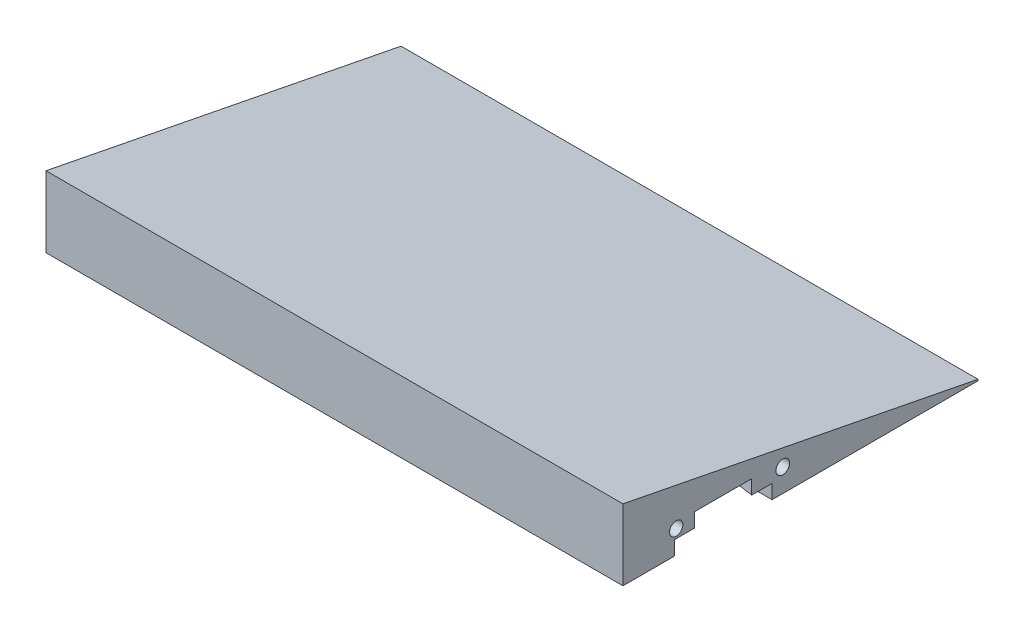
SolidWorks part; units mm, degrees
ref_plane "Front Plane" through (0, 0, 0) normal (0, 0, 1) x (1, 0, 0)
ref_plane "Top Plane" through (0, 0, 0) normal (0, 1, 0) x (1, 0, 0)
ref_plane "Right Plane" through (0, 0, 0) normal (1, 0, 0) x (0, 0, -1)
sketch "Sketch1" plane through (0, 0, 0) normal (1, 0, 0) x (0, 0, -1)
  line L0 (0, 0) -> (0, 20.32)
  line L1 (0, 20.32) -> (101.6, 0.4)
  line L2 (101.6, 0.4) -> (101.6, 0)
  line L3 (101.6, 0) -> (0, 0)
  dimension "D1" = 0.4
  dimension "D2" = 101.6
  dimension "D3" = 20.32
extrude "Boss-Extrude1" add sketch "Sketch1" along normal mid plane 391.16
sketch "Sketch2" plane through (195.58, 0, 0) normal (1, 0, 0) x (0, 0, -1)
  line L0 (0, 0) -> (101.6, 0) construction
  line L3 (0, 20.32) -> (0, 0) construction
  circle A0 centre (9.652, 3.81) radius 3.3147
  circle A1 centre (47.752, 3.81) radius 3.3147
  circle A3 centre (9.652, 3.81) radius 3.81 construction
  dimension "D1" = 38.1
  dimension "D2" = 6.6294
  dimension "D3" = 9.652
  dimension "D4" = 3.81
extrude "Cut-Extrude1" cut sketch "Sketch2" against normal blind 38.1
mirror "Mirror3" about plane through (0, 0, 0) normal (1, 0, 0) of "Cut-Extrude1"
sketch "Sketch3" plane through (-195.58, 0, 0) normal (-1, 0, 0) x (0, 0, 1)
  line L5 (0, 0) -> (-101.6, 0) construction
  line L6 (-42.672, 4.064) -> (-14.732, 4.064)
  line L7 (-42.672, 4.064) -> (-42.672, 0)
  line L8 (-42.672, 0) -> (-14.732, 0)
  line L9 (-14.732, 4.064) -> (-14.732, 0)
  line L10 (0, 20.32) -> (0, 0) construction
  dimension "D1" = 27.94
  dimension "D2" = 4.064
  dimension "D3" = 0
  dimension "D4" = 14.732
extrude "Cut-Extrude2" cut sketch "Sketch3" against normal through all
sketch "Sketch4" plane through (0, 0, 0) normal (0, -1, 0) x (1, 0, 0)
  line L0 (-144.78, -42.672) -> (-146.1056, -52.1043)
  line L1 (195.58, -42.672) -> (-195.58, -42.672) construction
  line L2 (-144.78, -42.672) -> (-128.5844, -42.672)
  line L5 (-144.78, -42.672) -> (-144.78, -52.1043) construction
  line L6 (-128.5844, -42.672) -> (-127.2588, -52.1043)
  line L7 (-128.5844, -42.672) -> (-128.5844, -52.1043) construction
  line L8 (-144.78, -52.1043) -> (-128.5844, -52.1043)
  line L9 (-144.78, -52.1043) -> (-146.1056, -52.1043)
  line L10 (-128.5844, -52.1043) -> (-127.2588, -52.1043)
  line L11 (-195.58, -42.672) -> (-195.58, -101.6) construction
  line L12 (-77.5812, -42.672) -> (-78.9069, -52.1043)
  line L13 (-77.5812, -52.1043) -> (-78.9069, -52.1043)
  line L14 (-77.5812, -52.1043) -> (-61.3857, -52.1043)
  line L15 (-61.3857, -52.1043) -> (-60.0601, -52.1043)
  line L16 (-61.3857, -42.672) -> (-60.0601, -52.1043)
  line L17 (-77.5812, -42.672) -> (-61.3857, -42.672)
  line L18 (-10.3825, -42.672) -> (-11.7081, -52.1043)
  line L19 (-10.3825, -52.1043) -> (-11.7081, -52.1043)
  line L20 (-10.3825, -52.1043) -> (5.8131, -52.1043)
  line L21 (5.8131, -52.1043) -> (7.1387, -52.1043)
  line L22 (5.8131, -42.672) -> (7.1387, -52.1043)
  line L23 (-10.3825, -42.672) -> (5.8131, -42.672)
  line L24 (56.8163, -42.672) -> (55.4906, -52.1043)
  line L25 (56.8163, -52.1043) -> (55.4906, -52.1043)
  line L26 (56.8163, -52.1043) -> (73.0118, -52.1043)
  line L27 (73.0118, -52.1043) -> (74.3374, -52.1043)
  line L28 (73.0118, -42.672) -> (74.3374, -52.1043)
  line L29 (56.8163, -42.672) -> (73.0118, -42.672)
  line L30 (124.015, -42.672) -> (122.6894, -52.1043)
  line L31 (124.015, -52.1043) -> (122.6894, -52.1043)
  line L32 (124.015, -52.1043) -> (140.2106, -52.1043)
  line L33 (140.2106, -52.1043) -> (141.5362, -52.1043)
  line L34 (140.2106, -42.672) -> (141.5362, -52.1043)
  line L35 (124.015, -42.672) -> (140.2106, -42.672)
  line L42 (195.58, -14.732) -> (-195.58, -14.732) construction
  line L52 (124.015, -14.732) -> (140.2106, -14.732)
  line L53 (140.2106, -14.732) -> (141.5362, -5.2997)
  line L54 (140.2106, -5.2997) -> (141.5362, -5.2997)
  line L55 (124.015, -5.2997) -> (140.2106, -5.2997)
  line L56 (124.015, -5.2997) -> (122.6894, -5.2997)
  line L57 (124.015, -14.732) -> (122.6894, -5.2997)
  line L58 (56.8163, -14.732) -> (73.0118, -14.732)
  line L59 (73.0118, -14.732) -> (74.3374, -5.2997)
  line L60 (73.0118, -5.2997) -> (74.3374, -5.2997)
  line L61 (56.8163, -5.2997) -> (73.0118, -5.2997)
  line L62 (56.8163, -5.2997) -> (55.4906, -5.2997)
  line L63 (56.8163, -14.732) -> (55.4906, -5.2997)
  line L64 (-10.3825, -14.732) -> (5.8131, -14.732)
  line L65 (5.8131, -14.732) -> (7.1387, -5.2997)
  line L66 (5.8131, -5.2997) -> (7.1387, -5.2997)
  line L67 (-10.3825, -5.2997) -> (5.8131, -5.2997)
  line L68 (-10.3825, -5.2997) -> (-11.7081, -5.2997)
  line L69 (-10.3825, -14.732) -> (-11.7081, -5.2997)
  line L70 (-77.5812, -14.732) -> (-61.3857, -14.732)
  line L71 (-61.3857, -14.732) -> (-60.0601, -5.2997)
  line L72 (-61.3857, -5.2997) -> (-60.0601, -5.2997)
  line L73 (-77.5812, -5.2997) -> (-61.3857, -5.2997)
  line L74 (-77.5812, -5.2997) -> (-78.9069, -5.2997)
  line L75 (-77.5812, -14.732) -> (-78.9069, -5.2997)
  line L76 (-144.78, -14.732) -> (-128.5844, -14.732)
  line L77 (-128.5844, -14.732) -> (-127.2588, -5.2997)
  line L78 (-128.5844, -5.2997) -> (-127.2588, -5.2997)
  line L79 (-144.78, -5.2997) -> (-128.5844, -5.2997)
  line L80 (-144.78, -5.2997) -> (-146.1056, -5.2997)
  line L81 (-144.78, -14.732) -> (-146.1056, -5.2997)
  line L83 (-195.58, -28.702) -> (195.58, -28.702) construction
  line L84 (-195.58, -14.732) -> (-195.58, -42.672) construction
  line L85 (195.58, -14.732) -> (195.58, -42.672) construction
  line L86 (195.58, -14.732) -> (-195.58, -14.732) construction
  dimension "D1" = 8
  dimension "D2" = 8
  dimension "D3" = 18.8468
  dimension "D4" = 9.525
  dimension "D5" = 50.8
  dimension "D7" = 51.0032
  dimension "D8" = 13.97
  dimension "D9" = 0
  dimension "D10" = 0
  dimension "D11" = 0
  dimension "D12" = 0
  dimension "D13" = 0
  dimension "D6" = 5
extrude "Cut-Extrude3" cut sketch "Sketch4" against normal blind 4.064
sketch "Sketch7" plane through (195.58, 0, 0) normal (1, 0, 0) x (0, 0, -1)
  line L1 (0, 0) -> (101.6, 0)
  line L2 (0, 0) -> (0, 20.54)
  line L3 (0, 20.54) -> (101.6, 20.54)
  line L4 (101.6, 0) -> (101.6, 20.54)
extrude "Cut-Extrude5" cut sketch "Sketch7" against normal blind 226.06
sketch "Sketch9" plane through (0, 4.064, 0) normal (0, -1, 0) x (1, 0, 0)
  line L0 (-30.48, -20.447) -> (-39.9123, -19.1214)
  line L1 (-30.48, -42.672) -> (-30.48, -14.732) construction
  line L2 (-39.9123, -19.1214) -> (-39.9123, -38.1714)
  line L3 (-39.9123, -38.1714) -> (-30.48, -36.8458)
  line L4 (-30.48, -36.8458) -> (-30.48, -20.447)
  line L5 (-30.48, -20.447) -> (-39.9123, -20.447) construction
  line L6 (-30.48, -36.8458) -> (-39.9123, -36.8458) construction
  line L7 (-30.48, -14.732) -> (-61.3857, -14.732) construction
  point P10 (0, 0)
  point P13 (0, 0)
  dimension "D1" = 8
  dimension "D2" = 8
  dimension "D3" = 9.525
  dimension "D4" = 19.05
  dimension "D5" = 5.715
extrude "Cut-Extrude6" cut sketch "Sketch9" against normal blind 4.064
sketch "Sketch10" plane through (-30.48, 0, 0) normal (1, 0, 0) x (0, 0, -1)
  line L0 (0, 20.32) -> (0, 0) construction
  line L1 (20.447, 4.064) -> (14.732, 4.064) construction
  line L2 (42.672, 4.064) -> (36.8458, 4.064) construction
  circle A0 centre (15.24, 6.604) radius 1.905
  circle A1 centre (45.72, 6.604) radius 1.9499
  dimension "D5" = 3.81
  dimension "D6" = 3.8998
  dimension "D1" = 15.24
  dimension "D2" = 30.48
  dimension "D3" = 2.54
  dimension "D4" = 2.54
extrude "Cut-Extrude7" cut sketch "Sketch10" against normal blind 12.7
